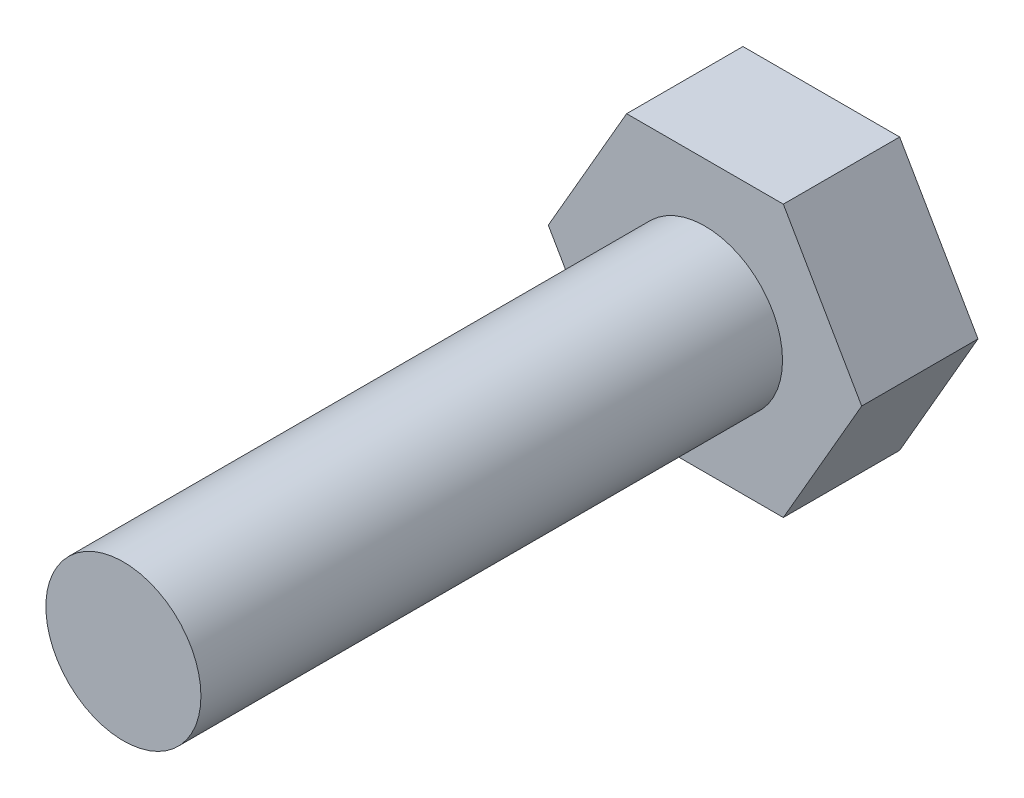
SolidWorks part; units mm, degrees
material "AISI Type A2 Tool Steel"
ref_plane "Front Plane" through (0, 0, 0) normal (0, 0, 1) x (1, 0, 0)
ref_plane "Top Plane" through (0, 0, 0) normal (0, 1, 0) x (1, 0, 0)
ref_plane "Right Plane" through (0, 0, 0) normal (1, 0, 0) x (0, 0, -1)
sketch "Sketch1" plane through (0, 0, 0) normal (0, 0, 1) x (1, 0, 0)
  line L1 (4.0415, 0) -> (2.0207, 3.5)
  line L2 (2.0207, 3.5) -> (-2.0207, 3.5)
  line L3 (-2.0207, 3.5) -> (-4.0415, 0)
  line L4 (-4.0415, 0) -> (-2.0207, -3.5)
  line L5 (-2.0207, -3.5) -> (2.0207, -3.5)
  line L6 (2.0207, -3.5) -> (4.0415, 0)
  circle A0 centre (0, 0) radius 3.5 construction
  dimension "D1" = 7
  dimension "D2" = 7
extrude "Boss-Extrude1" add sketch "Sketch1" along normal blind 3 contours L2 L3 L4 L5 L6 L1
sketch "Sketch2" plane through (0, 0, 3) normal (0, 0, 1) x (1, 0, 0)
  circle A0 centre (0, 0) radius 2
  dimension "D1" = 4
extrude "Boss-Extrude2" add sketch "Sketch2" along normal blind 15
